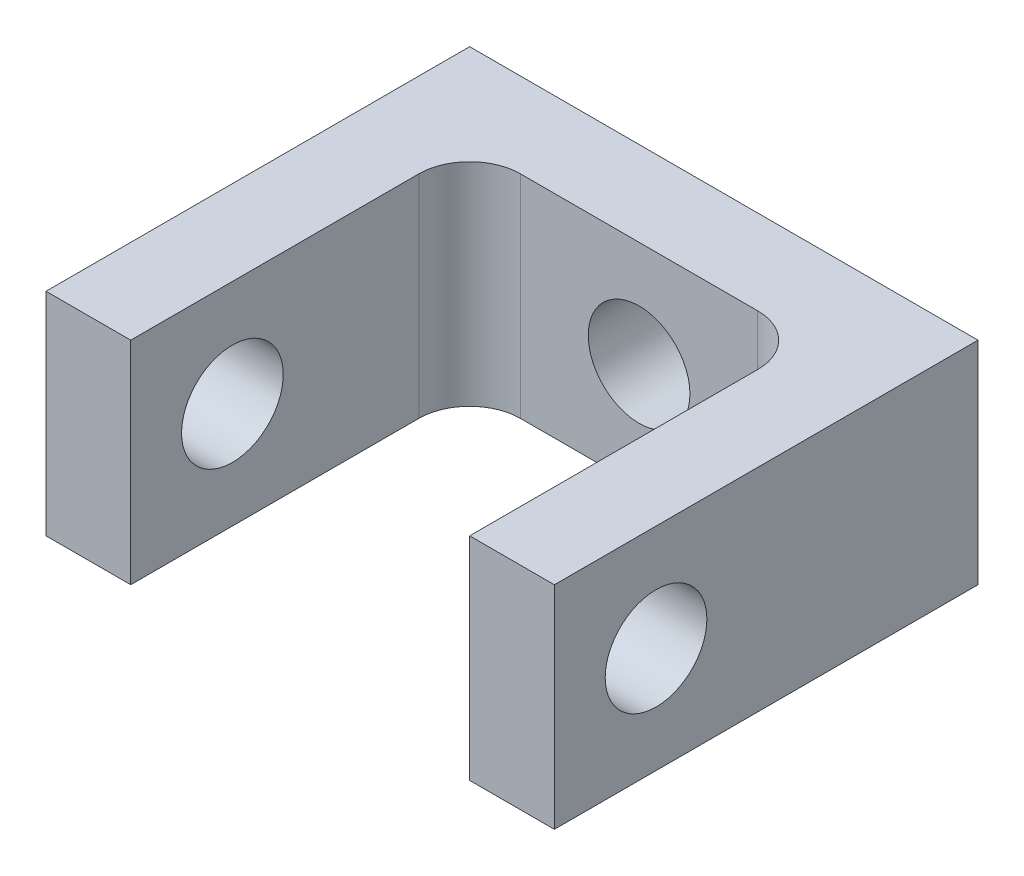
SolidWorks part; units mm, degrees
ref_plane "Płaszczyzna przednia" through (0, 0, 0) normal (0, 0, 1) x (1, 0, 0)
ref_plane "Płaszczyzna górna" through (0, 0, 0) normal (0, 1, 0) x (1, 0, 0)
ref_plane "Płaszczyzna prawa" through (0, 0, 0) normal (1, 0, 0) x (0, 0, -1)
sketch "Szkic1" plane through (0, 0, 0) normal (0, 0, 1) x (1, 0, 0)
  line L1 (30, 12.5) -> (-30, 12.5)
  line L2 (30, 12.5) -> (30, -12.5)
  line L3 (30, -12.5) -> (-30, -12.5)
  line L4 (-30, 12.5) -> (-30, -12.5)
  line L5 (30, 12.5) -> (-30, -12.5) construction
  line L6 (30, -12.5) -> (-30, 12.5) construction
  circle A0 centre (0, 0) radius 6
  dimension "D1" = 60
  dimension "D3" = 12
  dimension "D2" = 25
extrude "Dodanie-wyciągnięcie1" add sketch "Szkic1" along normal blind 10
sketch "Szkic2" plane through (0, 0, 10) normal (0, 0, 1) x (1, 0, 0)
  line L0 (-30, -12.5) -> (30, -12.5) construction
  line L1 (-30, 12.5) -> (-20, 12.5)
  line L2 (-30, 12.5) -> (-30, -12.5)
  line L3 (-30, -12.5) -> (-20, -12.5)
  line L4 (-20, 12.5) -> (-20, -12.5)
  line L6 (30, 12.5) -> (20, 12.5)
  line L7 (30, 12.5) -> (30, -12.5)
  line L8 (30, -12.5) -> (20, -12.5)
  line L9 (20, 12.5) -> (20, -12.5)
  dimension "D1" = 10
  dimension "D2" = 10
extrude "Dodanie-wyciągnięcie2" add sketch "Szkic2" along normal blind 40
fillet "Zaokrąglenie1" radius 6 2 edges at (20, 0, 10) (-20, 0, 10)
sketch "Szkic3" plane through (-30, 0, 0) normal (-1, 0, 0) x (0, 0, 1)
  line L0 (0, 12.5) -> (0, -12.5) construction
  line L1 (50, 12.5) -> (0, 12.5) construction
  circle A0 centre (38, 0) radius 6
  dimension "D1" = 38
  dimension "D2" = 12
  dimension "D3" = 12.5
extrude "Wytnij-wyciągnięcie1" cut sketch "Szkic3" against normal blind 70
